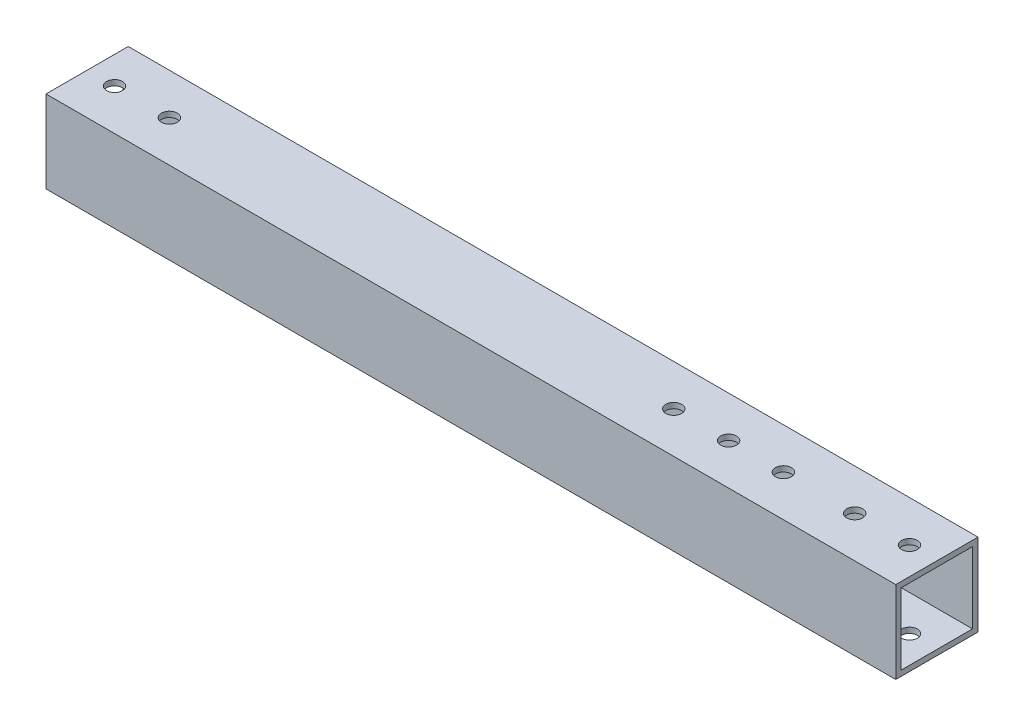
SolidWorks part; units mm, degrees
material "Thornel Mat VMA"
ref_plane "前视基准面" through (0, 0, 0) normal (0, 0, 1) x (1, 0, 0)
ref_plane "上视基准面" through (0, 0, 0) normal (0, 1, 0) x (1, 0, 0)
ref_plane "右视基准面" through (0, 0, 0) normal (1, 0, 0) x (0, 0, -1)
other "Configuration Table"
sketch "草图1" plane through (0, 0, 0) normal (1, 0, 0) x (0, 0, -1)
  line L0 (-6.5, -6.5) -> (-6.5, 6.5)
  line L1 (-7.5, -7.5) -> (7.5, -7.5)
  line L2 (-7.5, -7.5) -> (-7.5, 7.5)
  line L3 (-7.5, 7.5) -> (7.5, 7.5)
  line L4 (7.5, -7.5) -> (7.5, 7.5)
  line L5 (-7.5, -7.5) -> (7.5, 7.5) construction
  line L6 (-7.5, 7.5) -> (7.5, -7.5) construction
  line L7 (-6.5, 6.5) -> (6.5, 6.5)
  line L8 (6.5, -6.5) -> (6.5, 6.5)
  line L9 (-6.5, -6.5) -> (6.5, -6.5)
  point P0 (0, 0)
  dimension "D1" = 15
  dimension "D2" = 15
  dimension "D3" = 1
extrude "凸台-拉伸1" add sketch "草图1" along normal blind 155
sketch "草图2" plane through (0, 7.5, 0) normal (0, 1, 0) x (1, 0, 0)
  line L0 (0, 0) -> (199.7777, 0) construction
  circle A0 centre (5, 0) radius 1.45 construction
  circle A1 centre (15, 0) radius 1.45 construction
  circle A2 centre (140, 0) radius 1.45 construction
  circle A3 centre (150, 0) radius 1.45 construction
  circle A4 centre (5, 0) radius 1.45
  circle A5 centre (15, 0) radius 1.45
  circle A6 centre (140, 0) radius 1.45
  circle A7 centre (150, 0) radius 1.45
  circle A8 centre (127, 0) radius 1.45
  circle A9 centre (117, 0) radius 1.45
  circle A10 centre (107, 0) radius 1.45
  dimension "D1" = 13
  dimension "D2" = 10
  dimension "D3" = 10
extrude "切除-拉伸1" cut sketch "草图2" against normal through all
